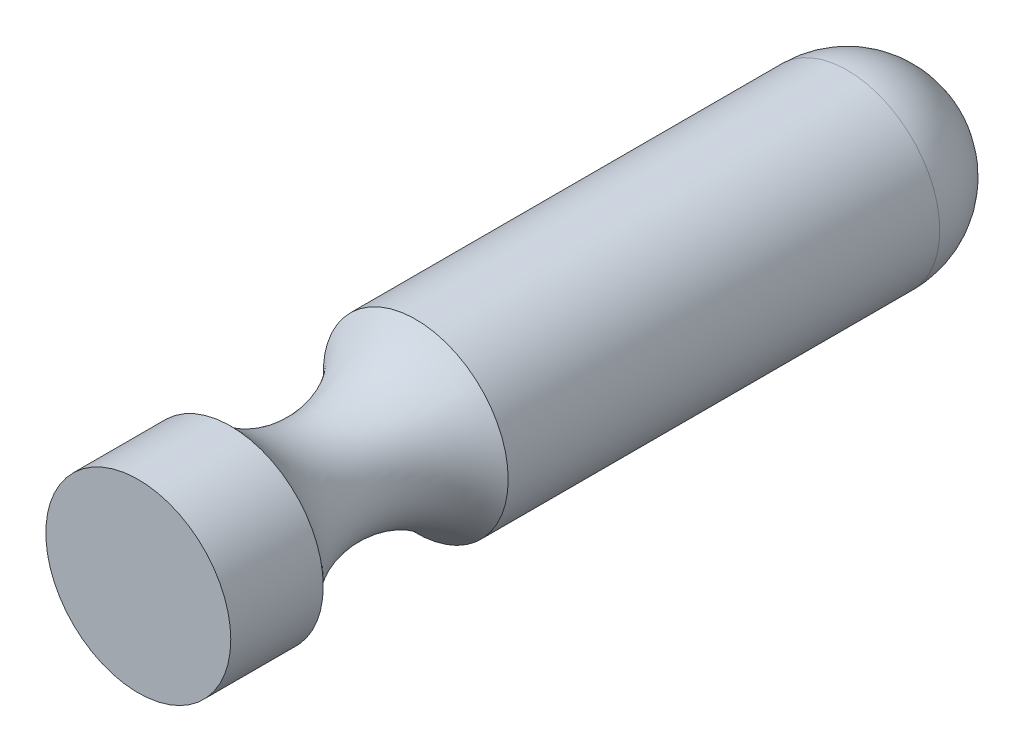
SolidWorks part; units mm, degrees
material "Acrylic (Medium-high impact)"
ref_plane "Front Plane" through (0, 0, 0) normal (0, 0, 1) x (1, 0, 0)
ref_plane "Top Plane" through (0, 0, 0) normal (0, 1, 0) x (1, 0, 0)
ref_plane "Right Plane" through (0, 0, 0) normal (1, 0, 0) x (0, 0, -1)
sketch "Sketch1" plane through (0, 0, 0) normal (0, 1, 0) x (1, 0, 0)
  line L0 (2.6581, -68.2256) -> (2.6581, 96.8744)
  line L1 (2.6581, -68.2256) -> (21.7081, -68.2256)
  line L2 (21.7081, -68.2256) -> (21.7081, -49.1756)
  line L5 (21.7081, -11.0756) -> (21.7081, 77.8244)
  arc A0 (2.6581, 96.8744) -> (21.7081, 77.8244) centre (2.6581, 77.8244) cw
  arc A1 (21.7081, -11.0756) -> (21.7081, -49.1756) centre (38.5087, -30.1256) ccw
  dimension "D4" = 19.05
  dimension "D5" = 25.4
  dimension "D1" = 165.1
  dimension "D2" = 19.05
  dimension "D3" = 19.05
  dimension "D6" = 38.1
revolve "Revolve1" add sketch "Sketch1" angle 360 about L0
